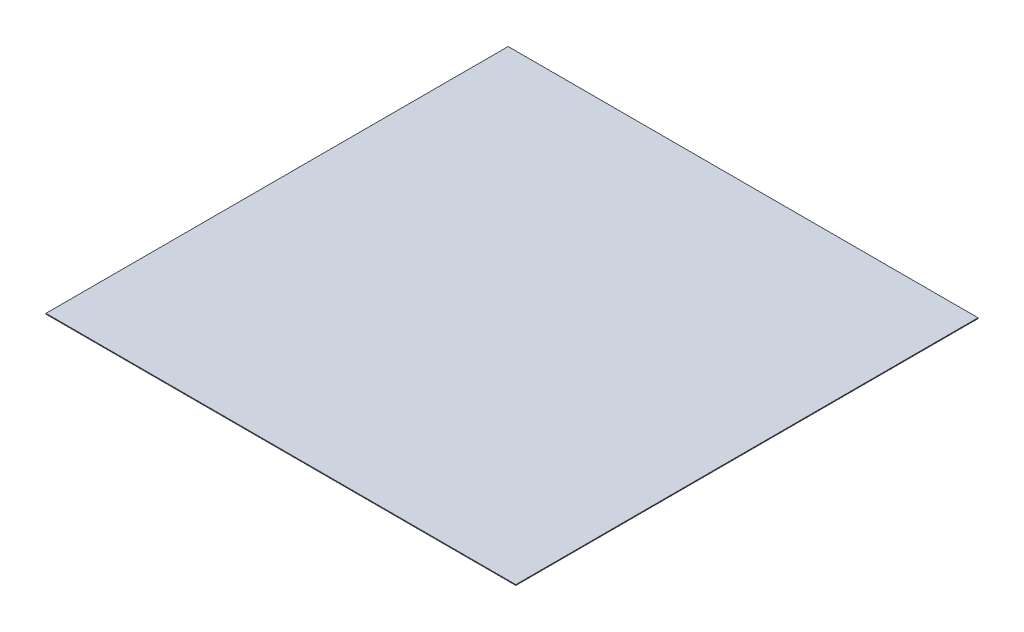
SolidWorks part; units mm, degrees
material "Plain Carbon Steel"
ref_plane "Front Plane" through (0, 0, 0) normal (0, 0, 1) x (1, 0, 0)
ref_plane "Top Plane" through (0, 0, 0) normal (0, 1, 0) x (1, 0, 0)
ref_plane "Right Plane" through (0, 0, 0) normal (1, 0, 0) x (0, 0, -1)
sketch "Sketch1" plane through (0, 0, 0) normal (0, 1, 0) x (1, 0, 0)
  line L1 (-610, -600) -> (610, -600)
  line L2 (-610, -600) -> (-610, 600)
  line L3 (-610, 600) -> (610, 600)
  line L4 (610, -600) -> (610, 600)
  line L5 (-610, -600) -> (610, 600) construction
  line L6 (-610, 600) -> (610, -600) construction
  point P0 (0, 0)
  dimension "D1" = 1220
  dimension "D2" = 1200
extrude "Boss-Extrude1" add sketch "Sketch1" along normal blind 2
